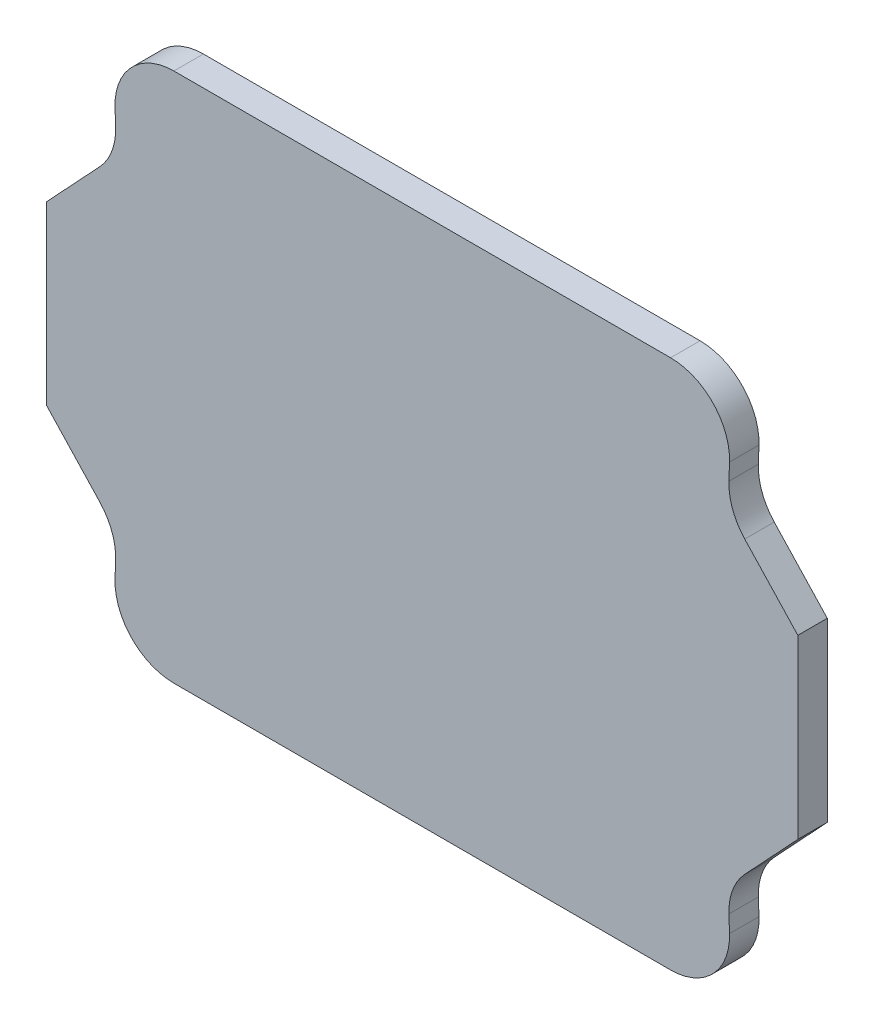
SolidWorks part; units mm, degrees
ref_plane "Front Plane" through (0, 0, 0) normal (0, 0, 1) x (1, 0, 0)
ref_plane "Top Plane" through (0, 0, 0) normal (0, 1, 0) x (1, 0, 0)
ref_plane "Right Plane" through (0, 0, 0) normal (1, 0, 0) x (0, 0, -1)
sketch "Sketch1" plane through (0, 0, 0) normal (0, 0, 1) x (1, 0, 0)
  line L0 (-266.7, 0) -> (266.7, 0)
  line L1 (266.7, 0) -> (263.7119, 88.0362)
  line L2 (263.7119, 88.0362) -> (323.85, 152.4)
  line L3 (323.85, 152.4) -> (323.85, 304.8)
  line L4 (0, 0) -> (0, 457.2) construction
  line L5 (-323.85, 228.6) -> (0, 228.6) construction
  line L6 (-266.7, 457.2) -> (266.7, 457.2)
  line L7 (266.7, 457.2) -> (263.7119, 369.1638)
  line L8 (263.7119, 369.1638) -> (323.85, 304.8)
  line L9 (-266.7, 457.2) -> (-263.7119, 369.1638)
  line L10 (-263.7119, 369.1638) -> (-323.85, 304.8)
  line L11 (-323.85, 152.4) -> (-323.85, 304.8)
  line L12 (-263.7119, 88.0362) -> (-323.85, 152.4)
  line L13 (-266.7, 0) -> (-263.7119, 88.0362)
  line L14 (0, 228.6) -> (323.85, 228.6) construction
  point P16 (0, 457.2)
  dimension "D1" = 647.7
  dimension "D2" = 135
  dimension "D3" = 533.4
  dimension "D4" = 152.4
  dimension "D5" = 457.2
extrude "Boss-Extrude1" add sketch "Sketch1" along normal blind 25.4
fillet "Fillet1" radius 50.8 8 edges at (266.7, 0, 12.7) (-266.7, 0, 12.7) (-263.7119, 88.0362, 12.7) (-263.7119, 369.1638, 12.7) (-266.7, 457.2, 12.7) (266.7, 457.2, 12.7) (263.7119, 88.0362, 12.7) (263.7119, 369.1638, 12.7)
